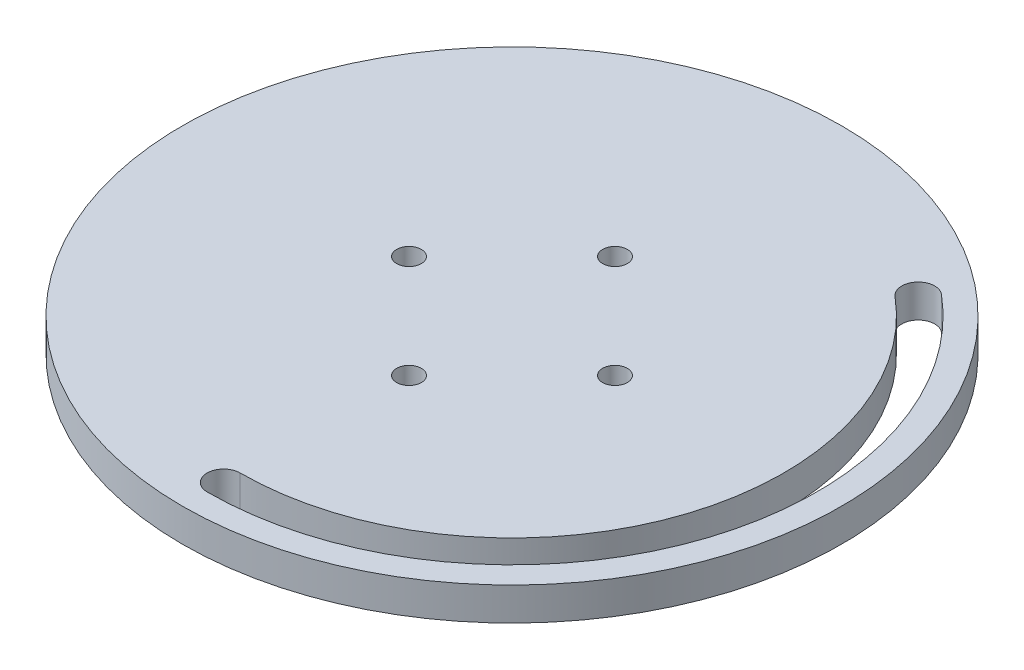
SolidWorks part; units mm, degrees
ref_plane "Front Plane" through (0, 0, 0) normal (0, 0, 1) x (1, 0, 0)
ref_plane "Top Plane" through (0, 0, 0) normal (0, 1, 0) x (1, 0, 0)
ref_plane "Right Plane" through (0, 0, 0) normal (1, 0, 0) x (0, 0, -1)
sketch "Sketch1" plane through (0, 0, 0) normal (0, 1, 0) x (1, 0, 0)
  line L0 (0, 0) -> (0, -40) construction
  line L1 (0, 0) -> (25.7115, 30.6418) construction
  circle A0 centre (0, 0) radius 40
  circle A3 centre (0, 0) radius 29.5 construction
  circle A4 centre (0, 0) radius 37 construction
  circle A5 centre (0, 0) radius 33 construction
  arc A6 (23.7831, 28.3436) -> (21.212, 25.2795) centre (22.4976, 26.8116) ccw
  arc A7 (0, -33) -> (0, -37) centre (0, -35) ccw
  arc A8 (0, -33) -> (21.212, 25.2795) centre (0, 0) ccw
  arc A9 (23.7831, 28.3436) -> (0, -37) centre (0, 0) cw
  circle A10 centre (0, 0) radius 12.5 construction
  circle A11 centre (0, -12.5) radius 1.5
  circle A12 centre (-12.5, 0) radius 1.5
  circle A13 centre (0, 12.5) radius 1.5
  circle A14 centre (12.5, 0) radius 1.5
  point P19 (-15.3478, -6.2204)
  point P22 (0, 0)
  point P28 (0, 0)
  dimension "D1" = 80
  dimension "D2" = 59
  dimension "D3" = 74
  dimension "D4" = 66
  dimension "D8" = 4
  dimension "D9" = 35
  dimension "D10" = 4
  dimension "D11" = 35
  dimension "D12" = 25
  dimension "D13" = 3
  dimension "D5" = 40
  dimension "D6" = 40
  dimension "D7" = 140
  dimension "D14" = 4
extrude "Boss-Extrude1" add sketch "Sketch1" along normal blind 4
